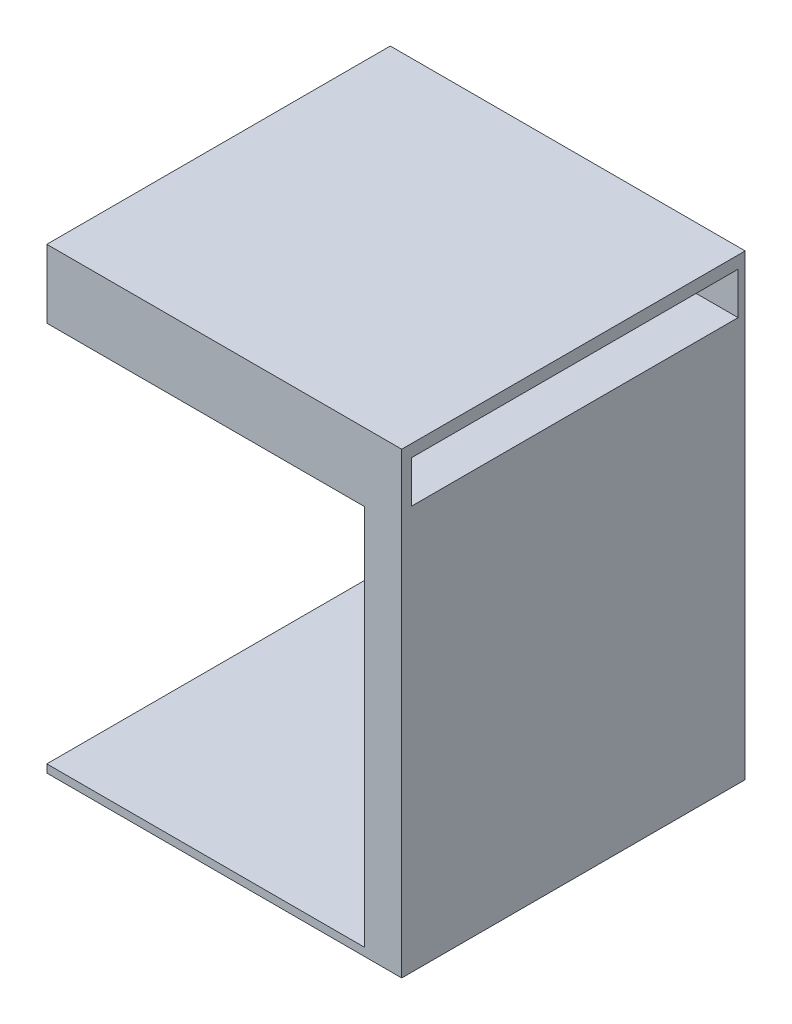
SolidWorks part; units mm, degrees
ref_plane "Front Plane" through (0, 0, 0) normal (0, 0, 1) x (1, 0, 0)
ref_plane "Top Plane" through (0, 0, 0) normal (0, 1, 0) x (1, 0, 0)
ref_plane "Right Plane" through (0, 0, 0) normal (1, 0, 0) x (0, 0, -1)
sketch "Sketch1" plane through (0, 0, 0) normal (0, 1, 0) x (1, 0, 0)
  line L1 (-46.5, 45) -> (46.5, 45)
  line L2 (-46.5, 45) -> (-46.5, -45)
  line L3 (-46.5, -45) -> (46.5, -45)
  line L4 (46.5, 45) -> (46.5, -45)
  line L5 (-46.5, 45) -> (46.5, -45) construction
  line L6 (-46.5, -45) -> (46.5, 45) construction
  point P0 (0, 0)
  dimension "D1" = 90
  dimension "D2" = 93
extrude "Boss-Extrude2" add sketch "Sketch1" along normal blind 120
sketch "Sketch4" plane through (0, 0, 45) normal (0, 0, 1) x (1, 0, 0)
  line L0 (-46.5, 120) -> (-46.5, 0) construction
  line L1 (-46.5, 102.0953) -> (36.6885, 102.0953)
  line L2 (-46.5, 102.0953) -> (-46.5, 2.0953)
  line L3 (-46.5, 2.0953) -> (36.6885, 2.0953)
  line L4 (36.6885, 102.0953) -> (36.6885, 2.0953)
  dimension "D1" = 100
extrude "Cut-Extrude2" cut sketch "Sketch4" against normal blind 86
sketch "Sketch6" plane through (46.5, 0, 0) normal (1, 0, 0) x (0, 0, -1)
  line L1 (-42.4103, 116.7856) -> (43.1441, 116.7856)
  line L2 (-42.4103, 116.7856) -> (-42.4103, 105.7856)
  line L3 (-42.4103, 105.7856) -> (43.1441, 105.7856)
  line L4 (43.1441, 116.7856) -> (43.1441, 105.7856)
  dimension "D1" = 11
extrude "Cut-Extrude4" cut sketch "Sketch6" against normal blind 86
sketch "Sketch8" plane through (-46.5, 0, 0) normal (-1, 0, 0) x (0, 0, 1)
  line L0 (-41, 102.0953) -> (45, 102.0953) construction
  line L1 (-35.6599, 108.5738) -> (38.7416, 108.5738)
  line L2 (-35.6599, 108.5738) -> (-35.6599, 102.0953)
  line L3 (-35.6599, 102.0953) -> (38.7416, 102.0953)
  line L4 (38.7416, 108.5738) -> (38.7416, 102.0953)
extrude "Cut-Extrude5" cut sketch "Sketch8" against normal blind 50 from offset 10
